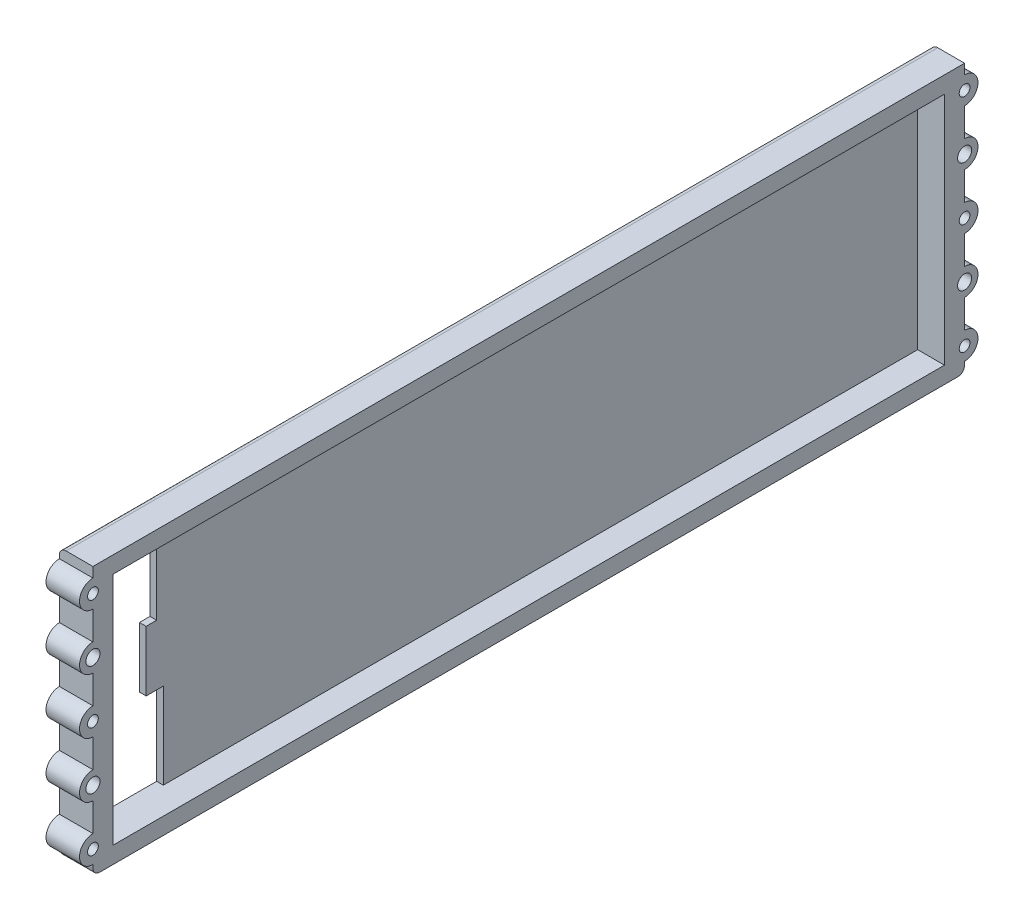
SolidWorks part; units mm, degrees
ref_plane "前视" through (0, 0, 0) normal (0, 0, 1) x (1, 0, 0)
ref_plane "上视" through (0, 0, 0) normal (0, 1, 0) x (1, 0, 0)
ref_plane "右视" through (0, 0, 0) normal (1, 0, 0) x (0, 0, -1)
sketch "草图1" plane through (0, 0, 0) normal (1, 0, 0) x (0, 0, -1)
  line L0 (-63, 18.5) -> (63, 18.5)
  line L1 (-62, 17.5) -> (62, 17.5)
  line L2 (-62, 17.5) -> (-62, -17.5)
  line L3 (-62, -17.5) -> (62, -17.5)
  line L4 (62, 17.5) -> (62, -17.5)
  line L5 (63, 18.5) -> (63, -18.5)
  line L6 (-63, -18.5) -> (63, -18.5)
  line L7 (-63, 18.5) -> (-63, -18.5)
  dimension "D1" = 124
  dimension "D2" = 35
  dimension "D3" = 17.5
  dimension "D4" = 62
  dimension "D5" = 1
extrude "凸台-拉伸1" add sketch "草图1" along normal blind 6
sketch "草图2" plane through (0, 0, 0) normal (-1, 0, 0) x (0, 0, 1)
  line L4 (63, -18.5) -> (63, 18.5)
  line L5 (63, 18.5) -> (-63, 18.5)
  line L6 (-63, 18.5) -> (-63, -18.5)
  line L7 (-63, -18.5) -> (63, -18.5)
  line L8 (63, -18.5) -> (63, 18.5)
  line L9 (63, 18.5) -> (-63, 18.5)
  line L10 (-63, 18.5) -> (-63, -18.5)
  line L11 (-63, -18.5) -> (63, -18.5)
  dimension "D1" = 0
extrude "凸台-拉伸2" add sketch "草图2" against normal blind 1
sketch "草图3" plane through (0, 0, -63) normal (0, 0, -1) x (-1, 0, 0)
  line L4 (0, -18.5) -> (0, 18.5)
  line L5 (0, 18.5) -> (-6, 18.5)
  line L6 (-6, 18.5) -> (-6, -18.5)
  line L7 (-6, -18.5) -> (0, -18.5)
  line L8 (0, -18.5) -> (0, 18.5)
  line L9 (0, 18.5) -> (-6, 18.5)
  line L10 (-6, 18.5) -> (-6, -18.5)
  line L11 (-6, -18.5) -> (0, -18.5)
  dimension "D1" = 0
extrude "凸台-拉伸3" add sketch "草图3" along normal blind 2
sketch "草图4" plane through (0, 0, 63) normal (0, 0, 1) x (1, 0, 0)
  line L4 (0, 18.5) -> (0, -18.5)
  line L5 (0, -18.5) -> (6, -18.5)
  line L6 (6, -18.5) -> (6, 18.5)
  line L7 (6, 18.5) -> (0, 18.5)
  line L8 (0, 18.5) -> (0, -18.5)
  line L9 (0, -18.5) -> (6, -18.5)
  line L10 (6, -18.5) -> (6, 18.5)
  line L11 (6, 18.5) -> (0, 18.5)
  dimension "D1" = 0
extrude "凸台-拉伸4" add sketch "草图4" along normal blind 2
sketch "草图10" plane through (0, 0, 0) normal (-1, 0, 0) x (0, 0, 1)
  line L0 (-65, -18.5) -> (-65, 18.5) construction
  circle A0 centre (-65, -16.5) radius 2
  dimension "D1" = 4
extrude "凸台-拉伸6" add sketch "草图10" against normal up to surface (6 mm away) up to face at (6, 0, 0)
pattern_linear "阵列(线性)1" count 5 spacing 8.25 along (0, 1, 0) of "凸台-拉伸6"
mirror "镜向2" about plane through (0, 0, 0) normal (0, 0, 1) of "阵列(线性)1", "凸台-拉伸6"
sketch "草图13" plane through (0, 0, 0) normal (-1, 0, 0) x (0, 0, 1)
  circle A0 centre (65, -16.5) radius 0.8
  circle A1 centre (65, 0) radius 0.8
  circle A2 centre (65, 16.5) radius 0.8
  dimension "D1" = 1.6
  dimension "D2" = 1.6
  dimension "D3" = 1.6
extrude "切除-拉伸4" cut sketch "草图13" against normal through all
sketch "草图14" plane through (0, 0, 0) normal (-1, 0, 0) x (0, 0, 1)
  circle A0 centre (65, -8.25) radius 2
  circle A1 centre (65, 8.25) radius 2
  arc A2 (65, 6.25) -> (65, 10.25) centre (65, 8.25) ccw construction
extrude "切除-拉伸5" cut sketch "草图14" against normal blind 1.5
sketch "草图15" plane through (1.5, 0, 0) normal (-1, 0, 0) x (0, 0, 1)
  circle A0 centre (65, -8.25) radius 1.05
  circle A1 centre (65, 8.25) radius 1.05
  dimension "D1" = 2.1
  dimension "D2" = 2.1
extrude "切除-拉伸6" cut sketch "草图15" against normal through all
mirror "镜向3" about plane through (0, 0, 0) normal (0, 0, 1) of "切除-拉伸4", "切除-拉伸6", "切除-拉伸5"
sketch "草图16" plane through (1, 0, 0) normal (1, 0, 0) x (0, 0, -1)
  line L0 (-65, 2) -> (-65, 6.25) construction
  line L1 (-61.5, 17) -> (-53.5613, 17)
  line L2 (-61.5, 17) -> (-61.5, -17)
  line L3 (-61.5, -17) -> (-53.5613, -17)
  line L4 (-53.5613, 17) -> (-53.5613, -9)
  line L5 (65, 18.5) -> (-65, 18.5) construction
  line L6 (-65, -18.5) -> (65, -18.5) construction
  line L8 (-65, 14.5) -> (-65, 10.25) construction
  line L9 (-53.5613, -17) -> (-53.5613, -9)
  line L10 (-53.5613, -17) -> (-51, -17)
  line L11 (-53.5613, -17) -> (-53.5613, -5.2)
  line L12 (-53.5613, -5.2) -> (-51, -5.2)
  line L13 (-53.5613, 17) -> (-53.5, 17)
  line L14 (-53.5613, 17) -> (-53.5613, -8)
  line L16 (-51, -5.2) -> (-51, -4)
  line L17 (-51, -17) -> (-51, -5.2)
  dimension "D1" = 3.5
  dimension "D2" = 1.5
  dimension "D3" = 1.5
  dimension "D5" = 14
  dimension "D6" = 11.8
extrude "切除-拉伸7" cut sketch "草图16" against normal blind 10
sketch "草图18" plane through (6, 0, 0) normal (1, 0, 0) x (0, 0, -1)
  line L1 (90.0753, -36.2782) -> (-94.98, -36.2782)
  line L2 (90.0753, -36.2782) -> (90.0753, 41.7537)
  line L3 (90.0753, 41.7537) -> (-94.98, 41.7537)
  line L4 (-94.98, -36.2782) -> (-94.98, 41.7537)
extrude "切除-拉伸8" cut sketch "草图18" against normal blind 1
sketch "草图19" plane through (0, 18.5, 0) normal (0, 1, 0) x (1, 0, 0)
  line L4 (5, -65) -> (5, 65)
  line L5 (5, 65) -> (0, 65)
  line L6 (0, 65) -> (0, -65)
  line L7 (0, -65) -> (5, -65)
  line L8 (5, -65) -> (5, 65)
  line L9 (5, 65) -> (0, 65)
  line L10 (0, 65) -> (0, -65)
  line L11 (0, -65) -> (5, -65)
  dimension "D1" = 0
extrude "凸台-拉伸7" add sketch "草图19" along normal blind 1.5
sketch "草图20" plane through (0, -18.5, 0) normal (0, -1, 0) x (1, 0, 0)
  line L4 (5, -65) -> (5, 65)
  line L5 (5, 65) -> (0, 65)
  line L6 (0, 65) -> (0, -65)
  line L7 (0, -65) -> (5, -65)
  line L8 (5, -65) -> (5, 65)
  line L9 (5, 65) -> (0, 65)
  line L10 (0, 65) -> (0, -65)
  line L11 (0, -65) -> (5, -65)
  dimension "D1" = 0
extrude "凸台-拉伸8" add sketch "草图20" along normal blind 1.5
sketch "草图21" plane through (0, 0, 0) normal (-1, 0, 0) x (0, 0, 1)
  line L0 (53.5613, -5.2) -> (51, -5.2) construction
  line L1 (61.5, 17) -> (52, 17)
  line L2 (61.5, 17) -> (61.5, 4.8)
  line L3 (61.5, 4.8) -> (52, 4.8)
  line L4 (52, 17) -> (52, 4.8)
  dimension "D1" = 9.5
  dimension "D2" = 10
extrude "切除-拉伸9" cut sketch "草图21" against normal blind 10
fillet "圆角1" radius 1 4 edges at (0, 20, 0) (0, -20, 0) (2.5, -20, 65) (2.5, -20, -65)
sketch "草图22" plane through (1, 0, 0) normal (1, 0, 0) x (0, 0, -1)
  line L0 (-61.5, -17) -> (-51, -17) construction
  line L1 (-61.5, -17) -> (-51, -17)
  line L2 (-61.5, 17) -> (-61.5, -17) construction
  line L3 (-61.5, 17) -> (-61.5, -17)
  line L4 (-61.5, 17) -> (-52, 17) construction
  line L5 (-61.5, 17) -> (-52, 17)
  line L6 (-52, 17) -> (-52, 4.8) construction
  line L7 (-52, 17) -> (-52, 4.8)
  line L8 (-52, 4.8) -> (-53.5613, 4.8) construction
  line L9 (-52, 4.8) -> (-53.5613, 4.8)
  line L10 (-53.5613, -5.2) -> (-53.5613, 4.8) construction
  line L11 (-53.5613, -5.2) -> (-53.5613, 4.8)
  line L12 (-53.5613, -5.2) -> (-51, -5.2) construction
  line L13 (-53.5613, -5.2) -> (-51, -5.2)
  line L14 (-51, -17) -> (-51, -5.2) construction
  line L15 (-51, -17) -> (-51, -5.2)
  line L16 (-62, 17.5) -> (-62, -17.5)
  line L17 (-62, -17.5) -> (-50.5, -17.5)
  line L18 (-50.5, -17.5) -> (-50.5, -4.7)
  line L19 (-53.0613, -4.7) -> (-50.5, -4.7)
  line L20 (-53.0613, -4.7) -> (-53.0613, 4.3)
  line L21 (-51.5, 4.3) -> (-53.0613, 4.3)
  line L22 (-51.5, 17.5) -> (-51.5, 4.3)
  line L23 (-62, 17.5) -> (-51.5, 17.5)
  dimension "D1" = 0.5
extrude "切除-拉伸10" cut sketch "草图22" against normal blind 10
sketch "草图23" plane through (1.5, 0, 0) normal (-1, 0, 0) x (0, 0, 1)
  circle A0 centre (-65, 8.25) radius 1.05 construction
  circle A1 centre (-65, 8.25) radius 1.05
  arc A2 (65, 10.25) -> (65, 6.25) centre (65, 8.25) ccw
  arc A3 (65, 6.25) -> (65, 10.25) centre (65, 8.25) ccw
  arc A4 (65, 10.25) -> (65, 6.25) centre (65, 8.25) ccw
  arc A5 (65, 6.25) -> (65, 10.25) centre (65, 8.25) ccw
  arc A6 (65, -6.25) -> (65, -10.25) centre (65, -8.25) ccw
  arc A7 (65, -10.25) -> (65, -6.25) centre (65, -8.25) ccw
  arc A8 (65, -6.25) -> (65, -10.25) centre (65, -8.25) ccw
  arc A9 (65, -10.25) -> (65, -6.25) centre (65, -8.25) ccw
  arc A10 (-65, -10.25) -> (-65, -6.25) centre (-65, -8.25) ccw
  arc A11 (-65, -6.25) -> (-65, -10.25) centre (-65, -8.25) ccw
  arc A12 (-65, -10.25) -> (-65, -6.25) centre (-65, -8.25) ccw
  arc A13 (-65, -6.25) -> (-65, -10.25) centre (-65, -8.25) ccw
  arc A14 (-65, 6.25) -> (-65, 10.25) centre (-65, 8.25) ccw
  arc A15 (-65, 10.25) -> (-65, 6.25) centre (-65, 8.25) ccw
  arc A16 (-65, 6.25) -> (-65, 10.25) centre (-65, 8.25) ccw
  arc A17 (-65, 10.25) -> (-65, 6.25) centre (-65, 8.25) ccw
  circle A18 centre (-65, -8.25) radius 1.05 construction
  circle A19 centre (-65, -8.25) radius 1.05
  circle A20 centre (65, -8.25) radius 1.05 construction
  circle A21 centre (65, -8.25) radius 1.05
  circle A22 centre (65, 8.25) radius 1.05 construction
  circle A23 centre (65, 8.25) radius 1.05
  dimension "D1" = 0
  dimension "D2" = 0
  dimension "D3" = 0
  dimension "D4" = 0
extrude "凸台-拉伸9" add sketch "草图23" along normal up to surface (1.5 mm away) up to face at (0, -0.1, 54.2653)
